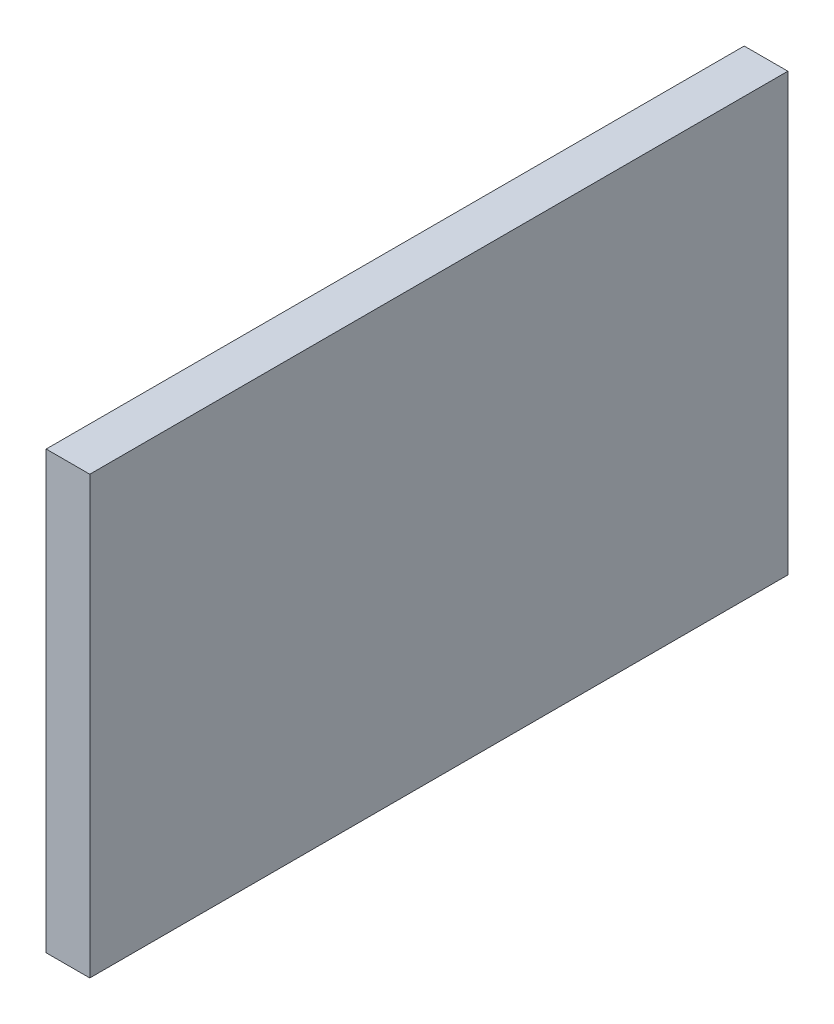
SolidWorks part; units mm, degrees
ref_plane "Front" through (0, 0, 0) normal (0, 0, 1) x (1, 0, 0)
ref_plane "Top" through (0, 0, 0) normal (0, 1, 0) x (1, 0, 0)
ref_plane "Right" through (0, 0, 0) normal (1, 0, 0) x (0, 0, -1)
sketch "Sketch1" plane through (0, 0, 0) normal (0, 1, 0) x (1, 0, 0)
  line L1 (-100, -1600) -> (100, -1600)
  line L2 (-100, -1600) -> (-100, 1600)
  line L3 (-100, 1600) -> (100, 1600)
  line L4 (100, -1600) -> (100, 1600)
  line L5 (-100, -1600) -> (100, 1600) construction
  line L6 (-100, 1600) -> (100, -1600) construction
  point P0 (0, 0)
  dimension "D1" = 200
  dimension "D2" = 3200
extrude "Boss-Extrude1" add sketch "Sketch1" along normal blind 2000
equation "\"D2@Sketch1\"=3000+1*\"D1@Sketch1\""
